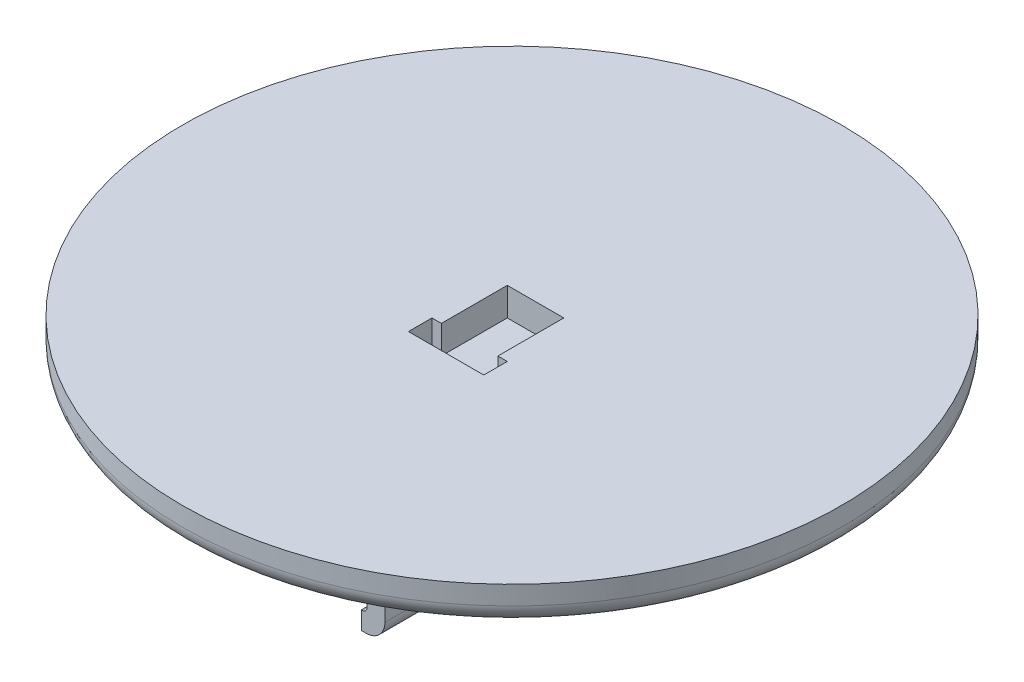
SolidWorks part; units mm, degrees
ref_plane "Front Plane" through (0, 0, 0) normal (0, 0, 1) x (1, 0, 0)
ref_plane "Top Plane" through (0, 0, 0) normal (0, 1, 0) x (1, 0, 0)
ref_plane "Right Plane" through (0, 0, 0) normal (1, 0, 0) x (0, 0, -1)
sketch "Sketch1" plane through (0, 0, 0) normal (0, 1, 0) x (1, 0, 0)
  circle A0 centre (0, 0) radius 35
extrude "Round Body" add sketch "Sketch1" along normal blind 4
fillet "Fillet1" radius 2 1 edges at (0, 0, 35)
sketch "Sketch2" plane through (0, 4, 0) normal (0, 1, 0) x (1, 0, 0)
  line L0 (0, 2.5) -> (0, 0) construction
  line L1 (-3, 2.5) -> (3, 2.5)
  line L2 (-3, 2.5) -> (-3, -4.5)
  line L3 (-3, -4.5) -> (3, -4.5)
  line L4 (3, 2.5) -> (3, -4.5)
  dimension "D1" = 6
  dimension "D2" = 7
  dimension "D3" = 2.5
extrude "Sensor Square Hole" cut sketch "Sketch2" against normal blind 3
sketch "Sketch4" plane through (0, 4, 0) normal (0, 1, 0) x (1, 0, 0)
  line L0 (-3, -4.5) -> (3, -4.5) construction
  line L1 (-4, -4.5) -> (4, -4.5)
  line L2 (-4, -4.5) -> (-4, -7)
  line L3 (-4, -7) -> (4, -7)
  line L4 (4, -4.5) -> (4, -7)
  line L5 (3, -4.5) -> (3, 2.5) construction
  point P4 (0, -4.5)
  point P7 (0, -4.5)
  dimension "D1" = 1
  dimension "D2" = 2.5
extrude "Sensor Lead Hole" cut sketch "Sketch4" against normal up to surface (4 mm away) up to face at (0, 0, 33)
sketch "Sketch5" plane through (0, 0, 0) normal (0, -1, 0) x (1, 0, 0)
  line L0 (0, 0) -> (0, -3) construction
  line L1 (-7.5, 21) -> (7.5, 21)
  line L2 (-7.5, 21) -> (-7.5, -3)
  line L3 (-7.5, -3) -> (7.5, -3)
  line L4 (7.5, 21) -> (7.5, -3)
  dimension "D1" = 15
  dimension "D2" = 24
  dimension "D3" = 3
extrude "Back Holder" add sketch "Sketch5" along normal blind 12
sketch "Sketch6" plane through (0, 0, 21) normal (0, 0, 1) x (1, 0, 0)
  line L0 (7.5, 0) -> (-7.5, 0) construction
  line L1 (-5.6, 0) -> (5.6, 0)
  line L2 (-5.6, 0) -> (-5.6, -10.1)
  line L3 (-5.6, -10.1) -> (5.6, -10.1)
  line L4 (5.6, 0) -> (5.6, -10.1)
  line L5 (7.5, -12) -> (-7.5, -12) construction
  line L6 (-7.5, -12) -> (-7.5, 0) construction
  line L7 (0, -10.1) -> (0, 0) construction
  dimension "D1" = 1.9
  dimension "D2" = 1.9
extrude "Holder Slot" cut sketch "Sketch6" against normal offset from surface (22 mm away) 2 up to face at (0, -6, -3)
fillet "Holder Rounds" radius 2 8 edges at (-7.5, 0, 9) (7.5, 0, 9) (-7.5, -6, -3) (0, -12, -3) (7.5, -6, -3) (0, 0, -3) (7.5, -12, 9) (-7.5, -12, 9)
sketch "Sketch7" plane through (0, 0, 21) normal (0, 0, 1) x (1, 0, 0)
  line L1 (-5, -10.1) -> (5, -10.1)
  line L2 (-5, -10.1) -> (-5, -12)
  line L3 (-5, -12) -> (5, -12)
  line L4 (5, -10.1) -> (5, -12)
  line L5 (5.5, -12) -> (-5.5, -12) construction
  line L6 (5.6, -10.1) -> (-5.6, -10.1) construction
  line L7 (-5.6, 0) -> (-5.6, -10.1) construction
  point P10 (0, 0)
  point P11 (0, -10.1)
  point P12 (0, -10.1)
  dimension "D1" = 0.6
extrude "Holder Top Removal" cut sketch "Sketch7" against normal up to surface (22 mm away) up to face at (0, -5.05, -1)
fillet "Holder Micro Top fillets" radius 0.5 2 edges at (5.6, -10.1, 10) (-5.6, -10.1, 10)
